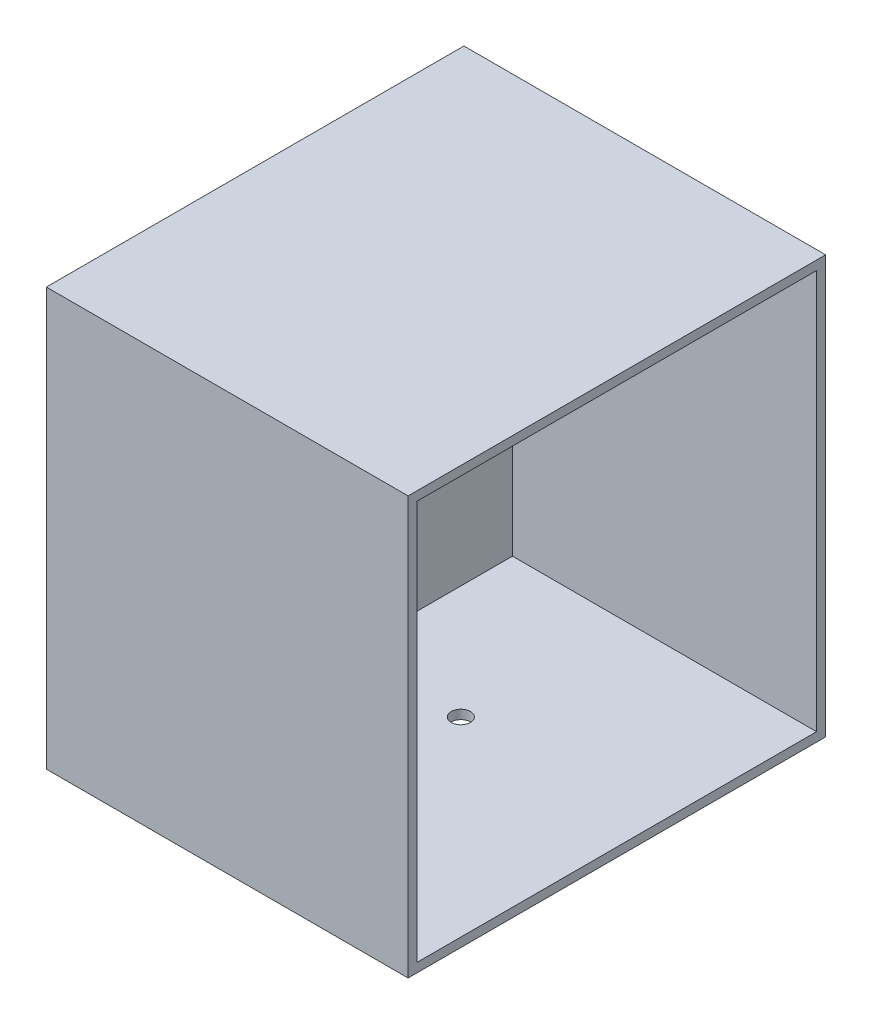
SolidWorks part; units mm, degrees
ref_plane "Front Plane" through (0, 0, 0) normal (0, 0, 1) x (1, 0, 0)
ref_plane "Top Plane" through (0, 0, 0) normal (0, 1, 0) x (1, 0, 0)
ref_plane "Right Plane" through (0, 0, 0) normal (1, 0, 0) x (0, 0, -1)
sketch "Sketch1" plane through (0, 0, 0) normal (1, 0, 0) x (0, 0, -1)
  line L1 (46, -46) -> (-46, -46)
  line L2 (46, -46) -> (46, 46)
  line L3 (46, 46) -> (-46, 46)
  line L4 (-46, -46) -> (-46, 46)
  line L5 (44, -44) -> (-44, -44)
  line L6 (44, -44) -> (44, 44)
  line L7 (44, 44) -> (-44, 44)
  line L8 (-44, -44) -> (-44, 44)
  circle A0 centre (0, 0) radius 27.305
  point P0 (0, 0)
  point P1 (0, 0)
  point P2 (0, 0)
  dimension "D5" = 54.61
  dimension "D1" = 92
  dimension "D2" = 92
  dimension "D3" = 88
  dimension "D4" = 88
extrude "Boss-Extrude1" add sketch "Sketch1" along normal blind 12.7 contours L8 L5 L6 L7 A0 | L4 L1 L2 L3 L5 L8 L7 L6
sketch "Sketch2" plane through (12.7, 0, 0) normal (1, 0, 0) x (0, 0, -1)
  line L1 (44, -44) -> (-44, -44)
  line L2 (44, -44) -> (44, 44)
  line L3 (44, 44) -> (-44, 44)
  line L4 (-44, -44) -> (-44, 44)
  line L5 (44, -44) -> (-44, 44) construction
  line L6 (44, 44) -> (-44, -44) construction
  point P0 (0, 0)
  line M4 (-46, 46) -> (-46, -46)
  line M5 (-46, -46) -> (46, -46)
  line M6 (46, -46) -> (46, 46)
  line M7 (46, 46) -> (-46, 46)
  dimension "D1" = 88
  dimension "D2" = 88
extrude "Boss-Extrude2" add sketch "Sketch2" along normal blind 67 contours L1 L4 L3 L2 M7 M4 M5 M6
hole_wizard "#19 (0.166) Diameter Hole1" positions "Sketch3" profile "Sketch4" hole size "#19" standard "ANSI Inch" end condition up to next
sketch "Sketch3" plane through (0, -46, 0) normal (0, -1, 0) x (-1, 0, 0)
  line L0 (-37.7, 7.62) -> (-79.7, 7.62)
  line L1 (-79.7, -46) -> (-79.7, 46) construction
  line L3 (-37.7, 7.62) -> (-37.7, 46)
  line L4 (-79.7, 46) -> (0, 46) construction
  line L6 (-37.7, -7.62) -> (-37.7, -46)
  line L7 (-79.7, -46) -> (0, -46) construction
  line L9 (-37.7, -7.62) -> (-79.7, -7.62)
  line L11 (0, 0) -> (-79.7, 0)
  line L12 (0, 46) -> (0, -46) construction
  line L13 (-37.7, 7.62) -> (-37.7, -7.62)
  point P0 (-37.7, 7.62)
  point P2 (-37.7, -7.62)
  point P34 (17.6007, 72.6138)
  point P37 (-37.7, 0)
  point P38 (-57.9732, -74.3506)
  point P41 (-79.7, -100.1157)
  point P43 (-40.4103, -84.3662)
  dimension "D1" = 42
  dimension "D2" = 42
  dimension "D3" = 15.24
  dimension "D4" = 0
sketch "Sketch4" plane through (37.7, -46, -7.62) normal (1, 0, 0) x (0, 0, -1)
  line L0 (0, 0) -> (0, 2)
  line L1 (0, 2) -> (2.1082, 2)
  line L2 (2.1082, 2) -> (2.1082, 0)
  line L5 (2.1082, 0) -> (0, 0)
  line L11 (0, -6.35) -> (0, 107.95) construction
  dimension "Thru Hole Dia." = 4.2164
  dimension "Thru Hole Depth" = 2
